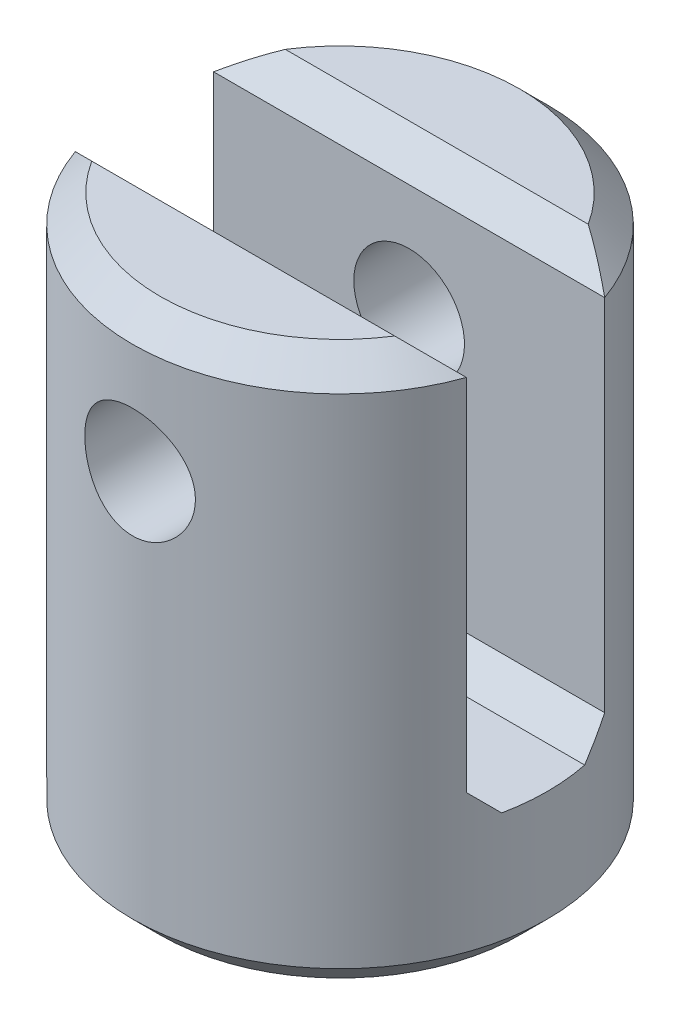
SolidWorks part; units mm, degrees
material "Aço cromo inoxidável"
ref_plane "Plano frontal" through (0, 0, 0) normal (0, 0, 1) x (1, 0, 0)
ref_plane "Plano superior" through (0, 0, 0) normal (0, 1, 0) x (1, 0, 0)
ref_plane "Plano direito" through (0, 0, 0) normal (1, 0, 0) x (0, 0, -1)
sketch "Esboço1" plane through (0, 0, 0) normal (0, 1, 0) x (1, 0, 0)
  circle A0 centre (0, 0) radius 7.5
  dimension "D1" = 15
extrude "Ressalto-extrusão1" add sketch "Esboço1" along normal mid plane 20
sketch "Esboço2" plane through (0, 0, 0) normal (1, 0, 0) x (0, 0, -1)
  line L0 (7.5, 10) -> (-7.5, 10) construction
  line L1 (-2.5, 10) -> (2.5, 10)
  line L2 (-2.5, 10) -> (-2.5, -5)
  line L3 (-2.5, -5) -> (2.5, -5)
  line L4 (2.5, 10) -> (2.5, -5)
  line L5 (0, -5) -> (0, 10) construction
  line L6 (-2.5, 2.5) -> (2.5, 2.5) construction
  point P568 (0, 2.5)
  dimension "D1" = 15
  dimension "D2" = 5
extrude "Corte-extrusão1" cut sketch "Esboço2" against normal through all both and the other way through all
sketch "Esboço3" plane through (0, 0, 0) normal (0, 0, 1) x (1, 0, 0)
  line L0 (0, 10) -> (0, 5) construction
  line L1 (7.0711, 10) -> (-7.0711, 10) construction
  circle A0 centre (0, 5) radius 2
  dimension "D1" = 4
  dimension "D2" = 5
extrude "Corte-extrusão2" cut sketch "Esboço3" against normal through all both and the other way through all
chamfer "Chanfro1" distance 1 angle 45 1 edges at (0, -10, 7.5)
chamfer "Chanfro2" distance 1 angle 45 4 edges at (0, 10, -7.5) (0, 10, -2.5) (0, 10, 2.5) (0, 10, 7.5)
chamfer "Chanfro3" distance 1 angle 45 2 edges at (0, -5, 2.5) (0, -5, -2.5)
